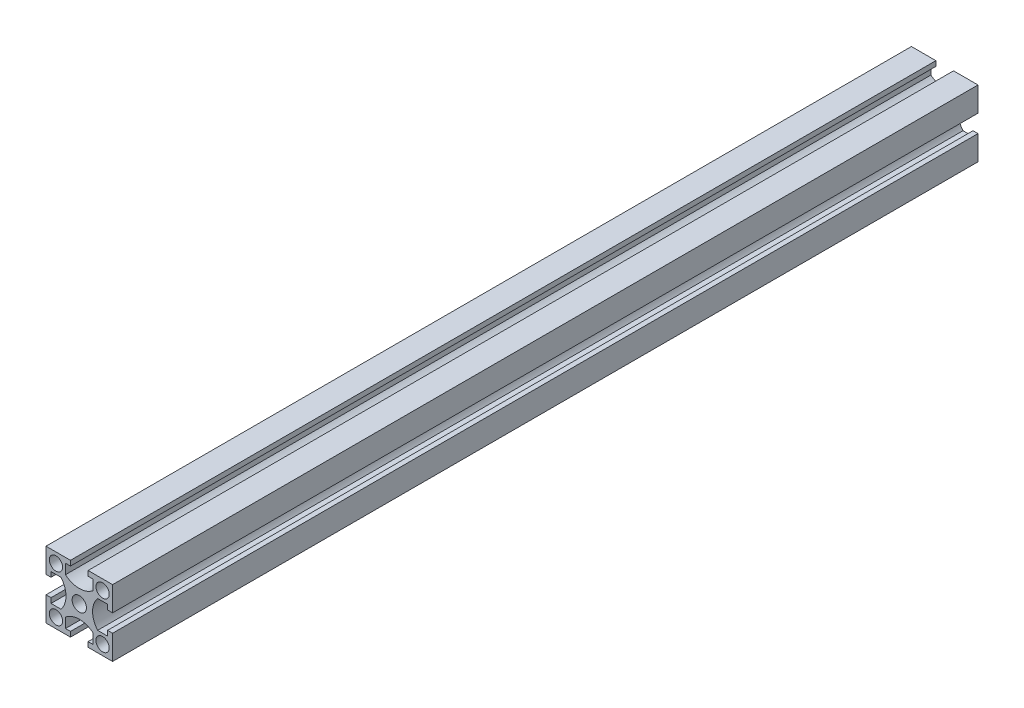
SolidWorks part; units mm, degrees
material "6061-T6 (SS)"
ref_plane "정면" through (0, 0, 0) normal (0, 0, 1) x (1, 0, 0)
ref_plane "윗면" through (0, 0, 0) normal (0, 1, 0) x (1, 0, 0)
ref_plane "우측면" through (0, 0, 0) normal (1, 0, 0) x (0, 0, -1)
sketch "스케치1" plane through (0, 0, 0) normal (0, 0, 1) x (1, 0, 0)
  line L1 (-10, 10) -> (10, 10)
  line L2 (-10, 10) -> (-10, -10)
  line L3 (-10, -10) -> (10, -10)
  line L4 (10, 10) -> (10, -10)
  line L5 (-10, 10) -> (10, -10) construction
  line L6 (-10, -10) -> (10, 10) construction
  point P0 (0, 0)
  dimension "D1" = 20
  dimension "D2" = 20
extrude "보스-돌출1" add sketch "스케치1" along normal blind 260
sketch "스케치2" plane through (0, 0, 260) normal (0, 0, 1) x (1, 0, 0)
  line L0 (-2.65, 10) -> (-2.65, 8.5)
  line L1 (10, 10) -> (-10, 10) construction
  line L2 (-2.65, 8.5) -> (-4.15, 8.5)
  line L3 (-4.15, 8.5) -> (-4.15, 5.5)
  line L4 (-2.65, 10) -> (2.65, 10)
  line L5 (2.65, 10) -> (2.65, 8.5)
  line L6 (2.65, 8.5) -> (4.15, 8.5)
  line L7 (4.15, 8.5) -> (4.15, 5.5)
  line L8 (10, 2.65) -> (8.5, 2.65)
  line L9 (8.5, 2.65) -> (8.5, 4.15)
  line L10 (8.5, 4.15) -> (5.5, 4.15)
  line L11 (10, 2.65) -> (10, -2.65)
  line L12 (10, -2.65) -> (8.5, -2.65)
  line L13 (8.5, -2.65) -> (8.5, -4.15)
  line L14 (8.5, -4.15) -> (5.5, -4.15)
  line L15 (2.65, -10) -> (2.65, -8.5)
  line L16 (2.65, -8.5) -> (4.15, -8.5)
  line L17 (4.15, -8.5) -> (4.15, -5.5)
  line L18 (2.65, -10) -> (-2.65, -10)
  line L19 (-2.65, -10) -> (-2.65, -8.5)
  line L20 (-2.65, -8.5) -> (-4.15, -8.5)
  line L21 (-4.15, -8.5) -> (-4.15, -5.5)
  line L22 (-10, -2.65) -> (-8.5, -2.65)
  line L23 (-8.5, -2.65) -> (-8.5, -4.15)
  line L24 (-8.5, -4.15) -> (-5.5, -4.15)
  line L25 (-10, -2.65) -> (-10, 2.65)
  line L26 (-10, 2.65) -> (-8.5, 2.65)
  line L27 (-8.5, 2.65) -> (-8.5, 4.15)
  line L28 (-8.5, 4.15) -> (-5.5, 4.15)
  arc A1 (-4.15, 5.5) -> (4.15, 5.5) centre (0, 10.4908) ccw
  arc A2 (5.5, 4.15) -> (5.5, -4.15) centre (10.4908, 0) ccw
  arc A3 (4.15, -5.5) -> (-4.15, -5.5) centre (0, -10.4908) ccw
  arc A4 (-5.5, -4.15) -> (-5.5, 4.15) centre (-10.4908, 0) ccw
  circle A5 centre (0, 0) radius 2.15
  circle A6 centre (-7, 7) radius 2
  circle A7 centre (7, 7) radius 2
  circle A8 centre (7, -7) radius 2
  circle A9 centre (-7, -7) radius 2
  point P4 (-2.65, 9.25)
  point P43 (0, 0)
  dimension "D2" = 1.5
  dimension "D8" = 4.3
  dimension "D9" = 4
  dimension "D10" = 4
  dimension "D11" = 4
  dimension "D12" = 4
  dimension "D1" = 5.3
  dimension "D3" = 8.3
  dimension "D4" = 4.15
  dimension "D5" = 2.65
  dimension "D6" = 4
  dimension "D7" = 3
  dimension "D13" = 14
  dimension "D14" = 7
  dimension "D15" = 7
  dimension "D16" = 7
  dimension "D17" = 14
  dimension "D18" = 7
  dimension "D19" = 7
  dimension "D20" = 7
extrude "컷-돌출1" cut sketch "스케치2" against normal through all
